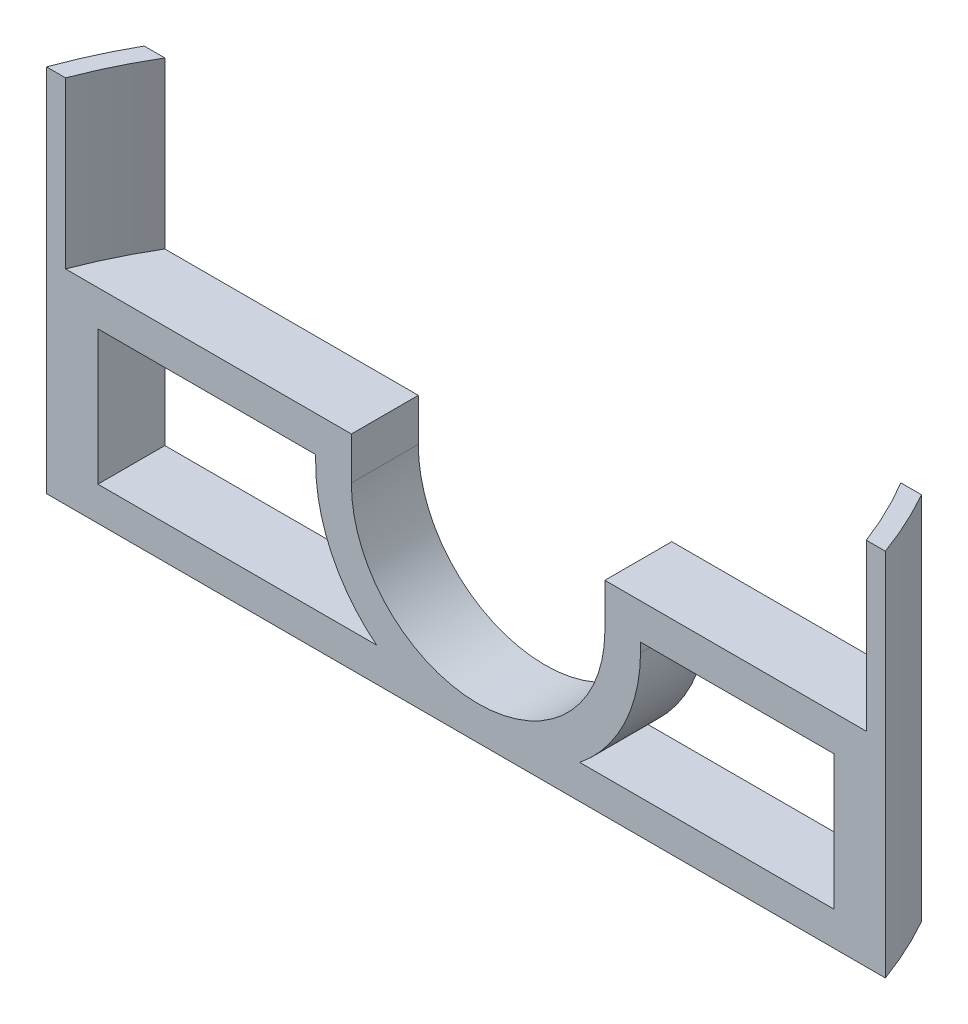
SolidWorks part; units mm, degrees
ref_plane "Front Plane" through (0, 0, 0) normal (0, 0, 1) x (1, 0, 0)
ref_plane "Top Plane" through (0, 0, 0) normal (0, 1, 0) x (1, 0, 0)
ref_plane "Right Plane" through (0, 0, 0) normal (1, 0, 0) x (0, 0, -1)
sketch "Sketch2" plane through (0, 0, 0) normal (0, 0, 1) x (1, 0, 0)
  line L2 (75.649, 29.0604) -> (108.082, 29.0604)
  line L4 (108.082, 29.0604) -> (108.082, 6.1826)
  line L5 (108.082, 6.1826) -> (12.082, 6.1826)
  line L7 (12.082, 6.1826) -> (12.082, 29.0604)
  line L8 (12.082, 29.0604) -> (47.2501, 29.0604)
  line L9 (47.2501, 24.3057) -> (47.2501, 29.0604)
  line L10 (75.649, 24.0596) -> (75.649, 29.0604)
  arc A2 (47.2501, 24.3057) -> (75.649, 24.0596) centre (61.4496, 24.1826) ccw
extrude "Boss-Extrude1" add sketch "Sketch2" along normal blind 7.5
sketch "Sketch6" plane through (0, 29.0604, 0) normal (0, 1, 0) x (1, 0, 0)
  line L0 (60.082, 25.4358) -> (60.082, -74.5642) construction
  line L5 (47.2501, 0) -> (12.082, 0)
  line L6 (12.082, 0) -> (12.082, -7.5)
  line L7 (12.082, -7.5) -> (47.2501, -7.5)
  line L8 (47.2501, -7.5) -> (47.2501, 0)
  line L9 (16.532, 0) -> (12.082, 0)
  line L10 (12.082, 0) -> (12.082, -7.5)
  line L11 (12.082, -7.5) -> (13.084, -7.5)
  line L13 (108.082, 0) -> (75.649, 0)
  line L14 (75.649, 0) -> (75.649, -7.5)
  line L15 (75.649, -7.5) -> (108.082, -7.5)
  line L16 (108.082, -7.5) -> (108.082, 0)
  line L17 (108.082, 0) -> (103.632, 0)
  line L19 (107.08, -7.5) -> (108.082, -7.5)
  line L20 (108.082, -7.5) -> (108.082, 0)
  arc A0 (16.532, 0) -> (13.084, -7.5) centre (60.082, -24.5642) ccw
  arc A1 (107.08, -7.5) -> (103.632, 0) centre (60.082, -24.5642) ccw
  dimension "D1" = 0
  dimension "D2" = 0
sketch "Sketch7" plane through (0, 29.0604, 0) normal (0, 1, 0) x (1, 0, 0)
  line L1 (47.2501, 0) -> (12.082, 0) construction
  line L3 (47.2501, -7.5) -> (12.082, -7.5) construction
  line L5 (108.082, 0) -> (75.649, 0) construction
  line L7 (108.082, -7.5) -> (75.649, -7.5) construction
  line L8 (101.3203, 0) -> (103.632, 0)
  line L9 (108.082, 0) -> (75.649, 0) construction
  line L10 (104.9464, -7.5) -> (107.08, -7.5)
  line L11 (108.082, -7.5) -> (75.649, -7.5) construction
  line L12 (18.8436, 0) -> (16.532, 0)
  line L13 (47.2501, 0) -> (12.082, 0) construction
  line L14 (15.2176, -7.5) -> (13.084, -7.5)
  line L15 (47.2501, -7.5) -> (12.082, -7.5) construction
  arc A4 (18.8436, 0) -> (15.2176, -7.5) centre (60.082, -24.5642) ccw
  arc A5 (104.9464, -7.5) -> (101.3203, 0) centre (60.082, -24.5642) ccw
  arc A10 (16.532, 0) -> (13.084, -7.5) centre (60.082, -24.5642) ccw
  arc A11 (107.08, -7.5) -> (103.632, 0) centre (60.082, -24.5642) ccw
  dimension "D2" = 100
extrude "Boss-Extrude2" add sketch "Sketch7" along normal blind 18.54 and the other way up to surface (22.8778 mm away) contours A5 L8 A11 L10 | A4 L14 A10 L12 other way up to face at (60.082, 6.1826, 3.75)
sketch "Sketch9" plane through (0, 29.0604, 0) normal (0, 1, 0) x (1, 0, 0)
  line L0 (108.082, 0) -> (103.632, 0) construction
  line L1 (107.08, -7.5) -> (108.082, -7.5) construction
  line L2 (108.082, -7.5) -> (108.082, 0) construction
  line L3 (12.082, -7.5) -> (13.084, -7.5) construction
  line L4 (16.532, 0) -> (12.082, 0) construction
  line L5 (12.082, 0) -> (12.082, -7.5) construction
  line L6 (108.082, 0) -> (103.632, 0)
  line L7 (107.08, -7.5) -> (108.082, -7.5)
  line L8 (108.082, -7.5) -> (108.082, 0)
  line L9 (12.082, -7.5) -> (13.084, -7.5)
  line L10 (16.532, 0) -> (12.082, 0)
  line L11 (12.082, 0) -> (12.082, -7.5)
  arc A0 (107.08, -7.5) -> (103.632, 0) centre (60.082, -24.5642) ccw construction
  arc A1 (16.532, 0) -> (13.084, -7.5) centre (60.082, -24.5642) ccw construction
  arc A2 (107.08, -7.5) -> (103.632, 0) centre (60.082, -24.5642) ccw
  arc A3 (16.532, 0) -> (13.084, -7.5) centre (60.082, -24.5642) ccw
extrude "Cut-Extrude2" cut sketch "Sketch9" against normal up to surface (22.8778 mm away) up to face at (60.082, 6.1826, 3.75)
sketch "Sketch8" plane through (0, 0, 7.5) normal (0, 0, 1) x (1, 0, 0)
  line L1 (18.8436, 29.0604) -> (18.8436, 47.6004) construction
  line L2 (61.3265, 9.9831) -> (61.3265, 31.383) construction
  line L4 (101.3203, 29.0604) -> (101.3203, 47.6004) construction
  line L66 (18.8436, 25.0604) -> (18.8436, 9.9831)
  line L67 (18.8436, 9.9831) -> (50.0648, 9.9831)
  line L68 (101.3203, 9.9831) -> (101.3203, 25.0604)
  line L69 (72.8344, 9.9831) -> (101.3203, 9.9831)
  line L70 (43.2501, 25.0604) -> (15.2176, 25.0604)
  line L71 (104.9464, 25.0604) -> (79.649, 25.0604)
  line L72 (79.649, 25.0604) -> (79.6489, 24.0249)
  line L73 (43.2501, 24.3057) -> (43.2501, 25.0604)
  line L74 (43.2501, 25.0604) -> (18.8436, 25.0604)
  line L75 (101.3203, 25.0604) -> (79.649, 25.0604)
  line L76 (79.649, 25.0604) -> (79.6489, 24.0249)
  line L77 (43.2501, 24.3057) -> (43.2501, 25.0604)
  arc A1 (47.2501, 24.3057) -> (75.649, 24.0596) centre (61.4496, 24.1826) ccw construction
  spline S0 degree 3 poles (79.6489, 24.0249) (79.3341, -12.3044) (43.0045, -12.0242) (43.2501, 24.3057) knots 0 0 0 0 1 1 1 1 weights 1 0.333968 0.333968 1
  spline S1 degree 3 poles (79.6489, 24.0249) (79.6058, 19.0522) (77.5954, 13.8004) (72.8344, 9.9831) knots 0 0 0 0 0.321967 0.321967 0.321967 0.321967 weights 1 0.78556 0.640162 0.563807
  spline S2 degree 3 poles (50.0648, 9.9831) (45.2101, 13.8756) (43.2159, 19.2473) (43.2501, 24.3057) knots 0.673696 0.673696 0.673696 0.673696 1 1 1 1 weights 0.560759 0.636258 0.782671 1
  dimension "D1" = 4
extrude "Cut-Extrude1" cut sketch "Sketch8" against normal up to surface (7.5 mm away) up to face at (60.5276, 29.4312, 0)
